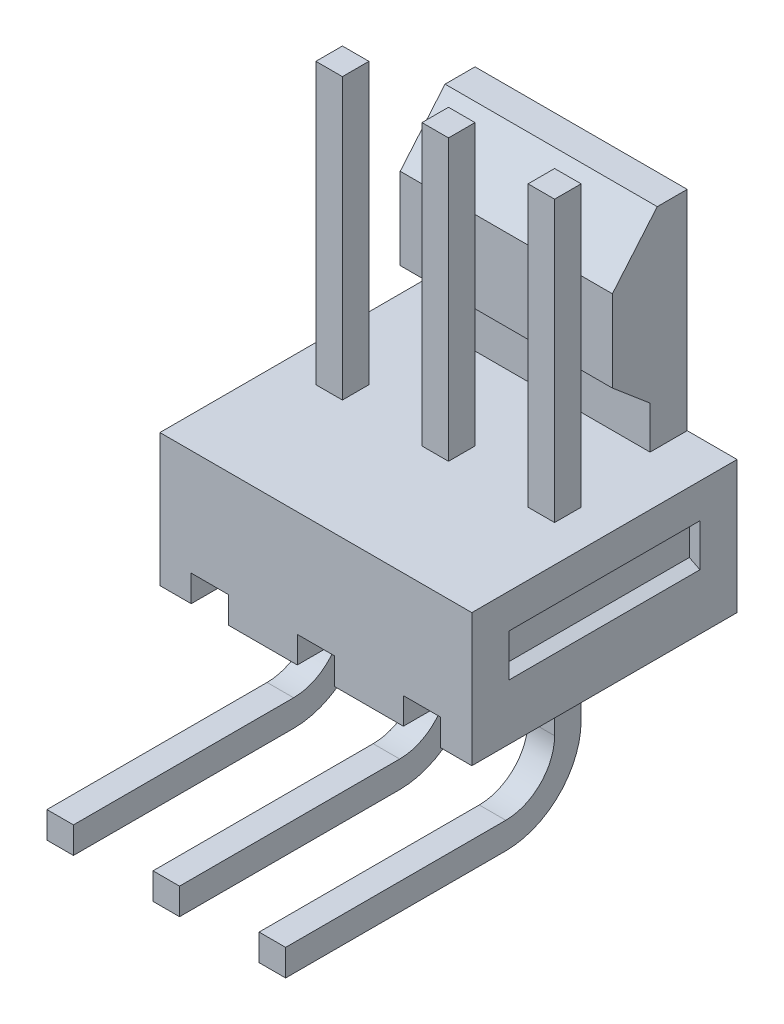
SolidWorks part; units mm, degrees
ref_plane "Front" through (0, 0, 0) normal (0, 0, 1) x (1, 0, 0)
ref_plane "Top" through (0, 0, 0) normal (0, 1, 0) x (1, 0, 0)
ref_plane "Right" through (0, 0, 0) normal (1, 0, 0) x (0, 0, -1)
ref_plane "Plane1" through (0, -1.5875, 0) normal (0, -1, 0) x (1, 0, 0)
sketch "Sketch1" plane through (0, -1.5875, 0) normal (0, -1, 0) x (1, 0, 0)
  line L0 (-3.7338, -3.175) -> (2.54, -3.175)
  line L1 (2.54, -3.175) -> (2.54, 3.175)
  line L2 (2.54, 3.175) -> (-3.7338, 3.175)
  line L3 (-3.7338, 3.175) -> (-3.7338, -3.175)
extrude "Boss-Extrude1" add sketch "Sketch1" against normal blind 3.175
ref_plane "Plane2" through (2.54, 0, 0) normal (1, 0, 0) x (0, 0, -1)
sketch "Sketch2" plane through (2.54, 0, 0) normal (1, 0, 0) x (0, 0, -1)
  line L0 (1.3843, 3.3655) -> (2.286, 2.6035)
  line L1 (2.286, 2.6035) -> (2.286, 1.5875)
  line L2 (2.286, 1.5875) -> (3.175, 1.5875)
  line L3 (3.175, 1.5875) -> (3.175, 6.5913)
  line L4 (3.175, 6.5913) -> (2.4575, 6.5913)
  line L5 (2.4575, 6.5913) -> (1.3843, 5.3213)
  line L6 (1.3843, 5.3213) -> (1.3843, 3.3655)
extrude "Boss-Extrude2" add sketch "Sketch2" against normal blind 5.08
sketch "Sketch3" plane through (2.54, 0, 0) normal (1, 0, 0) x (0, 0, -1)
  line L0 (-3.175, 1.5875) -> (3.175, 1.5875)
  line L1 (3.175, 1.5875) -> (3.175, -1.5875)
  line L2 (3.175, -1.5875) -> (-3.175, -1.5875)
  line L3 (-3.175, -1.5875) -> (-3.175, 1.5875)
extrude "Boss-Extrude3" add sketch "Sketch3" along normal blind 1.1938
sketch "Sketch4" plane through (0, 0, 3.175) normal (0, 0, 1) x (1, 0, 0)
  line L0 (-0.4445, -1.5875) -> (0.4445, -1.5875)
  line L1 (0.4445, -1.5875) -> (0.4445, -0.9525)
  line L2 (0.4445, -0.9525) -> (-0.4445, -0.9525)
  line L3 (-0.4445, -0.9525) -> (-0.4445, -1.5875)
extrude "Cut-Extrude1" cut sketch "Sketch4" against normal through all
sketch "Sketch5" plane through (0, -0.9525, 0) normal (0, -1, 0) x (1, 0, 0)
  line L0 (0.3175, -0.3175) -> (-0.3175, -0.3175)
  line L1 (-0.3175, -0.3175) -> (-0.3175, 0.3175)
  line L2 (-0.3175, 0.3175) -> (0.3175, 0.3175)
  line L3 (0.3175, 0.3175) -> (0.3175, -0.3175)
extrude "Boss-Extrude4" add sketch "Sketch5" along normal blind 3.683
sketch "Sketch6" plane through (0, 0, 0.3175) normal (0, 0, 1) x (1, 0, 0)
  line L0 (-0.3175, -4.0005) -> (0.3175, -4.0005)
  line L1 (0.3175, -4.0005) -> (0.3175, -4.6355)
  line L2 (0.3175, -4.6355) -> (-0.3175, -4.6355)
  line L3 (-0.3175, -4.6355) -> (-0.3175, -4.0005)
extrude "Boss-Extrude5" add sketch "Sketch6" along normal blind 6.4389
sketch "Sketch7" plane through (0, 0, 3.175) normal (0, 0, 1) x (1, 0, 0)
  line L0 (-2.9845, -1.5875) -> (-2.0955, -1.5875)
  line L1 (-2.0955, -1.5875) -> (-2.0955, -0.9525)
  line L2 (-2.0955, -0.9525) -> (-2.9845, -0.9525)
  line L3 (-2.9845, -0.9525) -> (-2.9845, -1.5875)
extrude "Cut-Extrude2" cut sketch "Sketch7" against normal through all
sketch "Sketch8" plane through (0, -0.9525, 0) normal (0, -1, 0) x (1, 0, 0)
  line L0 (-2.2225, -0.3175) -> (-2.8575, -0.3175)
  line L1 (-2.8575, -0.3175) -> (-2.8575, 0.3175)
  line L2 (-2.8575, 0.3175) -> (-2.2225, 0.3175)
  line L3 (-2.2225, 0.3175) -> (-2.2225, -0.3175)
extrude "Boss-Extrude6" add sketch "Sketch8" along normal blind 3.683
sketch "Sketch9" plane through (0, 0, 0.3175) normal (0, 0, 1) x (1, 0, 0)
  line L0 (-2.8575, -4.0005) -> (-2.2225, -4.0005)
  line L1 (-2.2225, -4.0005) -> (-2.2225, -4.6355)
  line L2 (-2.2225, -4.6355) -> (-2.8575, -4.6355)
  line L3 (-2.8575, -4.6355) -> (-2.8575, -4.0005)
extrude "Boss-Extrude7" add sketch "Sketch9" along normal blind 6.4389
sketch "Sketch10" plane through (0, 0, 3.175) normal (0, 0, 1) x (1, 0, 0)
  line L0 (2.0955, -1.5875) -> (2.9845, -1.5875)
  line L1 (2.9845, -1.5875) -> (2.9845, -0.9525)
  line L2 (2.9845, -0.9525) -> (2.0955, -0.9525)
  line L3 (2.0955, -0.9525) -> (2.0955, -1.5875)
extrude "Cut-Extrude3" cut sketch "Sketch10" against normal through all
sketch "Sketch11" plane through (0, -0.9525, 0) normal (0, -1, 0) x (1, 0, 0)
  line L0 (2.8575, -0.3175) -> (2.2225, -0.3175)
  line L1 (2.2225, -0.3175) -> (2.2225, 0.3175)
  line L2 (2.2225, 0.3175) -> (2.8575, 0.3175)
  line L3 (2.8575, 0.3175) -> (2.8575, -0.3175)
extrude "Boss-Extrude8" add sketch "Sketch11" along normal blind 3.683
sketch "Sketch12" plane through (0, 0, 0.3175) normal (0, 0, 1) x (1, 0, 0)
  line L0 (2.2225, -4.0005) -> (2.8575, -4.0005)
  line L1 (2.8575, -4.0005) -> (2.8575, -4.6355)
  line L2 (2.8575, -4.6355) -> (2.2225, -4.6355)
  line L3 (2.2225, -4.6355) -> (2.2225, -4.0005)
extrude "Boss-Extrude9" add sketch "Sketch12" along normal blind 6.4389
sketch "Sketch13" plane through (0, 1.5875, 0) normal (0, 1, 0) x (-1, 0, 0)
  line L0 (2.2225, -0.3175) -> (2.2225, 0.3175)
  line L1 (2.2225, 0.3175) -> (2.8575, 0.3175)
  line L2 (2.8575, 0.3175) -> (2.8575, -0.3175)
  line L3 (2.8575, -0.3175) -> (2.2225, -0.3175)
extrude "Boss-Extrude10" add sketch "Sketch13" along normal blind 6.7056
sketch "Sketch14" plane through (0, 1.5875, 0) normal (0, 1, 0) x (-1, 0, 0)
  line L0 (-0.3175, -0.3175) -> (-0.3175, 0.3175)
  line L1 (-0.3175, 0.3175) -> (0.3175, 0.3175)
  line L2 (0.3175, 0.3175) -> (0.3175, -0.3175)
  line L3 (0.3175, -0.3175) -> (-0.3175, -0.3175)
extrude "Boss-Extrude11" add sketch "Sketch14" along normal blind 6.7056
sketch "Sketch15" plane through (0, 1.5875, 0) normal (0, 1, 0) x (-1, 0, 0)
  line L0 (-2.8575, -0.3175) -> (-2.8575, 0.3175)
  line L1 (-2.8575, 0.3175) -> (-2.2225, 0.3175)
  line L2 (-2.2225, 0.3175) -> (-2.2225, -0.3175)
  line L3 (-2.2225, -0.3175) -> (-2.8575, -0.3175)
extrude "Boss-Extrude12" add sketch "Sketch15" along normal blind 6.7056
ref_plane "Plane3" through (0, 0, -2.286) normal (0, 0, -1) x (-1, 0, 0)
sketch "Sketch16" plane through (0, 0, -2.286) normal (0, 0, -1) x (-1, 0, 0)
  line L0 (3.7338, 0.762) -> (3.4798, 0.635)
  line L1 (3.4798, 0.635) -> (3.4798, -0.127)
  line L2 (3.4798, -0.127) -> (3.7338, -0.254)
  line L3 (3.7338, -0.254) -> (3.7338, 0.762)
extrude "Cut-Extrude4" cut sketch "Sketch16" against normal blind 4.572
sketch "Sketch17" plane through (0, 0, -2.286) normal (0, 0, -1) x (-1, 0, 0)
  line L0 (-3.7338, -0.254) -> (-3.4798, -0.127)
  line L1 (-3.4798, -0.127) -> (-3.4798, 0.635)
  line L2 (-3.4798, 0.635) -> (-3.7338, 0.762)
  line L3 (-3.7338, 0.762) -> (-3.7338, -0.254)
extrude "Cut-Extrude5" cut sketch "Sketch17" against normal blind 4.572
fillet "Fillet1" radius 1.1684 3 edges at (2.54, -4.0005, 0.3175) (0, -4.0005, 0.3175) (-2.54, -4.0005, 0.3175)
fillet "Fillet2" radius 1.8034 3 edges at (2.54, -4.6355, -0.3175) (-2.54, -4.6355, -0.3175) (0, -4.6355, -0.3175)
sketch "Sketch18" plane through (0, 0, 6.7564) normal (0, 0, 1) x (1, 0, 0)
  line L0 (-2.8575, -4.318) -> (2.8575, -4.318) construction
  line L1 (-2.8575, -4.0005) -> (-2.8575, -4.6355) construction
  line L2 (2.8575, -4.6355) -> (2.8575, -4.0005) construction
  line L3 (-2.54, -4.0005) -> (-2.54, -4.6355) construction
  line L4 (-2.2225, -4.0005) -> (-2.8575, -4.0005) construction
  line L5 (-2.8575, -4.6355) -> (-2.2225, -4.6355) construction
  line L6 (0, -4.0005) -> (0, -4.6355) construction
  line L7 (0.3175, -4.0005) -> (-0.3175, -4.0005) construction
  line L8 (-0.3175, -4.6355) -> (0.3175, -4.6355) construction
  line L9 (2.54, -4.0005) -> (2.54, -4.6355) construction
  line L10 (2.8575, -4.0005) -> (2.2225, -4.0005) construction
  line L11 (2.2225, -4.6355) -> (2.8575, -4.6355) construction
  circle A0 centre (-2.54, -4.318) radius 0.127 construction
  circle A1 centre (0, -4.318) radius 0.127 construction
  circle A2 centre (2.54, -4.318) radius 0.127 construction
  point P30 (-2.3821, -4.318)
  point P31 (-0.543, -4.318)
  point P32 (1.856, -4.318)
  point P33 (2.54, -4.318)
  point P34 (0, -4.318)
  point P35 (-2.54, -4.318)
  point P36 (-2.54, -4.318)
  dimension "D1" = 0.254
  dimension "D2" = 0.254
  dimension "D3" = 0.254
